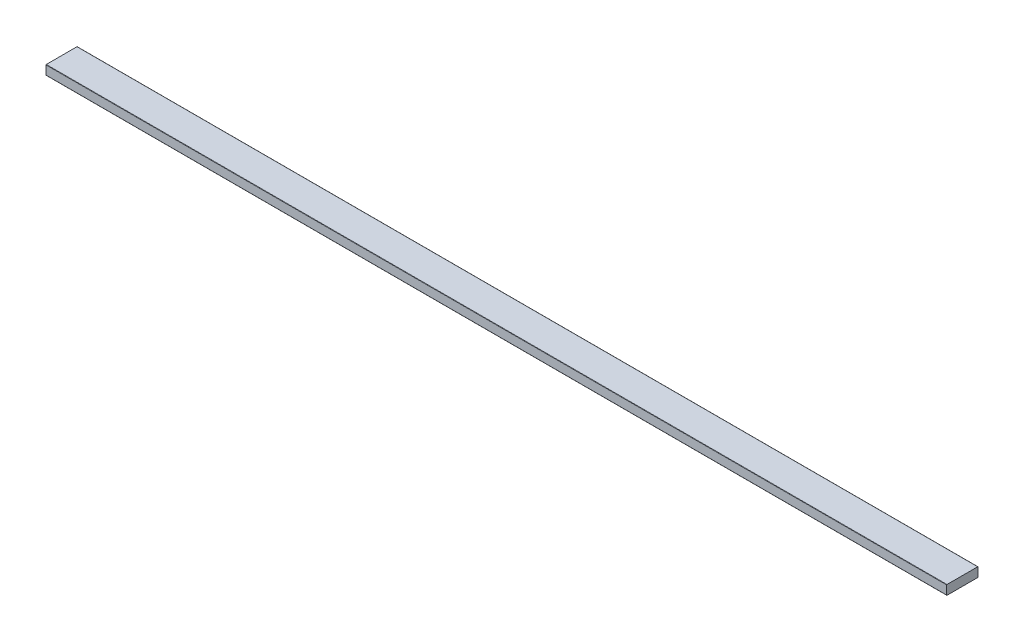
SolidWorks part; units mm, degrees
ref_plane "Front Plane" through (0, 0, 0) normal (0, 0, 1) x (1, 0, 0)
ref_plane "Top Plane" through (0, 0, 0) normal (0, 1, 0) x (1, 0, 0)
ref_plane "Right Plane" through (0, 0, 0) normal (1, 0, 0) x (0, 0, -1)
sketch "Sketch1" plane through (0, 0, 0) normal (0, 1, 0) x (1, 0, 0)
  line L1 (457.2, -15.875) -> (-457.2, -15.875)
  line L2 (457.2, -15.875) -> (457.2, 15.875)
  line L3 (457.2, 15.875) -> (-457.2, 15.875)
  line L4 (-457.2, -15.875) -> (-457.2, 15.875)
  line L5 (457.2, -15.875) -> (-457.2, 15.875) construction
  line L6 (457.2, 15.875) -> (-457.2, -15.875) construction
  point P0 (0, 0)
  dimension "Length" = 914.4
  dimension "Width" = 31.75
sketch "Sketch2" plane through (0, 0, 0) normal (1, 0, 0) x (0, 0, -1)
  line L0 (15.875, 4.7625) -> (15.875, -4.7625) construction
  point P2 (15.875, 0)
  dimension "Thickness" = 9.525
sketch "Sketch3" plane through (0, 0, 0) normal (0, 1, 0) x (1, 0, 0)
  line L1 (-457.2, 15.875) -> (457.2, 15.875)
  line L2 (-457.2, 15.875) -> (-457.2, -15.875)
  line L3 (-457.2, -15.875) -> (457.2, -15.875)
  line L4 (457.2, 15.875) -> (457.2, -15.875)
extrude "Boss-Extrude1" add sketch "Sketch3" against normal up to vertex (4.7625 mm away) and the other way up to vertex (4.7625 mm away) up to point (0, -4.7625, -15.875) other way up to point (0, 4.7625, -15.875)
fillet "Fillet1" radius 0.3143 4 edges at (0, -4.7625, 15.875) (0, -4.7625, -15.875) (0, 4.7625, -15.875) (0, 4.7625, 15.875)
equation "\"D1@Fillet1\" = \"Thickness@Sketch2\" * .033"
